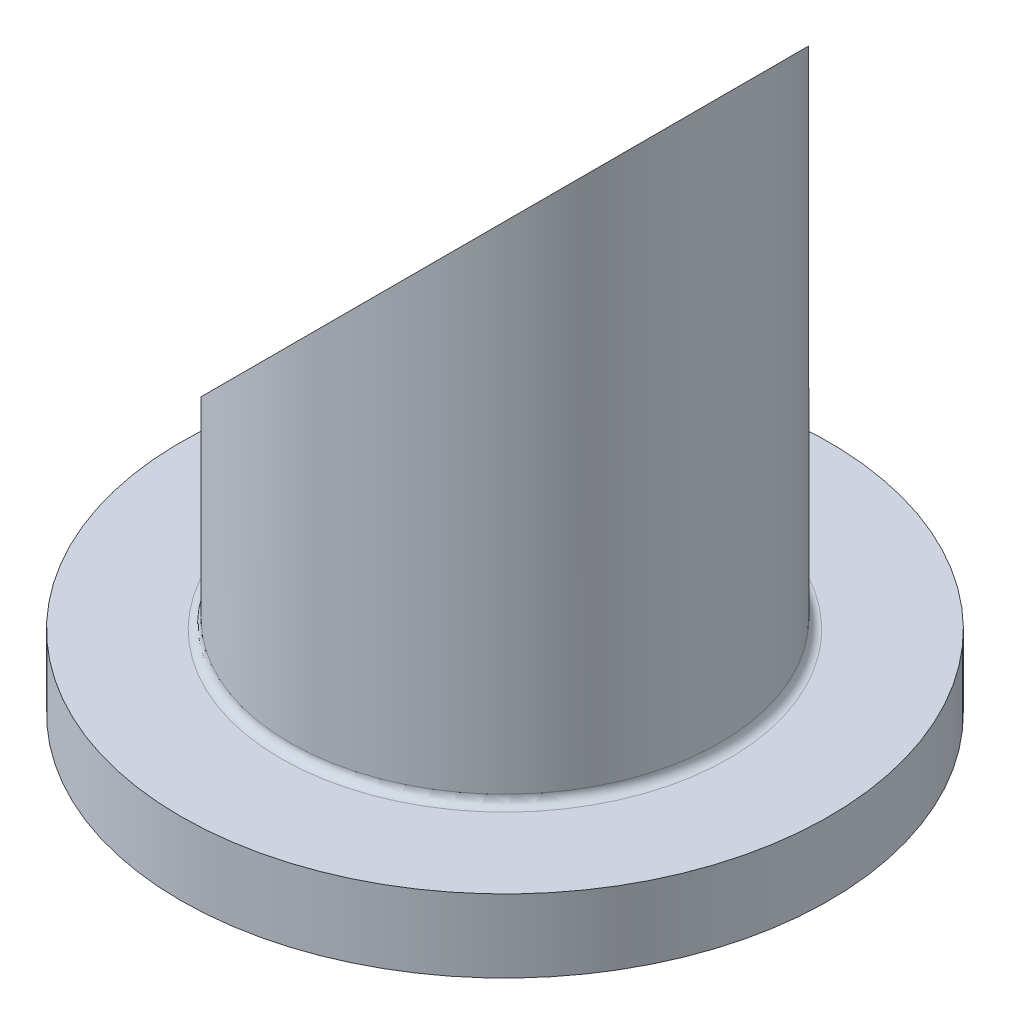
SolidWorks part; units mm, degrees
material "PTFE (general)"
ref_plane "Front Plane" through (0, 0, 0) normal (0, 0, 1) x (1, 0, 0)
ref_plane "Top Plane" through (0, 0, 0) normal (0, 1, 0) x (1, 0, 0)
ref_plane "Right Plane" through (0, 0, 0) normal (1, 0, 0) x (0, 0, -1)
sketch "Sketch1" plane through (0, 0, 0) normal (0, 1, 0) x (1, 0, 0)
  circle A0 centre (0, 0) radius 8.9
  dimension "D1" = 17.8
extrude "Boss-Extrude1" add sketch "Sketch1" along normal blind 2
sketch "Sketch2" plane through (0, 2, 0) normal (0, 1, 0) x (1, 0, 0)
  circle A0 centre (0, 0) radius 5.9
  dimension "D1" = 11.8
extrude "Boss-Extrude2" add sketch "Sketch2" along normal blind 20
sketch "Sketch3" plane through (0, 0, 0) normal (0, 0, 1) x (1, 0, 0)
  line L0 (-6.28, 5.42) -> (6.28, 17.98)
  line L2 (8.9, 2) -> (-8.9, 2) construction
  line L4 (-6.28, 5.42) -> (-6.28, 28.7719)
  line L5 (-6.28, 28.7719) -> (6.28, 28.7719)
  line L6 (6.28, 17.98) -> (6.28, 28.7719)
  point P2 (0, 11.7)
  dimension "D1" = 12.56
  dimension "D2" = 45
  dimension "D3" = 12.56
  dimension "D4" = 6.28
  dimension "D5" = 9.7
extrude "Cut-Extrude1" cut sketch "Sketch3" against normal through all both and the other way through all contours L0 L6 L5 L4
sketch "Sketch4" plane through (0, 0, 0) normal (0, -1, 0) x (1, 0, 0)
  line L1 (3, 0.5) -> (5, 0.5)
  line L2 (3, 0.5) -> (3, -0.5)
  line L3 (3, -0.5) -> (5, -0.5)
  line L4 (5, 0.5) -> (5, -0.5)
  dimension "D1" = 1
  dimension "D2" = 2
  dimension "D3" = 3
  dimension "D4" = 0.5
extrude "Cut-Extrude2" cut sketch "Sketch4" against normal blind 1.2
fillet "Fillet1" radius 0.25 12 edges at (4, 1.2, 0.5) (5, 1.2, 0) (4, 1.2, -0.5) (3, 1.2, 0) (3, 0.6, -0.5) (3, 0.6, 0.5) (5, 0.6, -0.5) (5, 0.6, 0.5) (4, 0, -0.5) (5, 0, 0) (3, 0, 0) (4, 0, 0.5)
fillet "Fillet2" radius 0.25 1 edges at (0, 2, 5.9)
